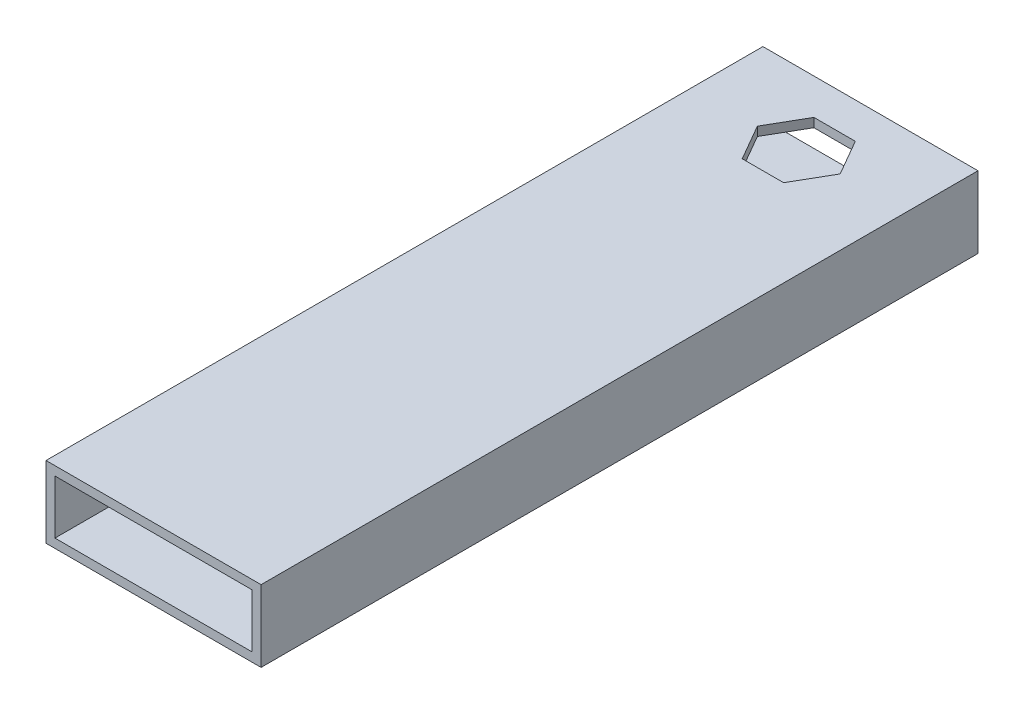
SolidWorks part; units mm, degrees
material "6061 Alloy"
ref_plane "Front Plane" through (0, 0, 0) normal (0, 0, 1) x (1, 0, 0)
ref_plane "Top Plane" through (0, 0, 0) normal (0, 1, 0) x (1, 0, 0)
ref_plane "Right Plane" through (0, 0, 0) normal (1, 0, 0) x (0, 0, -1)
sketch "Sketch1" plane through (0, 0, 0) normal (0, 0, 1) x (1, 0, 0)
  line L1 (0, 0) -> (38.1, 0)
  line L2 (0, 0) -> (0, 12.7)
  line L3 (0, 12.7) -> (38.1, 12.7)
  line L4 (38.1, 0) -> (38.1, 12.7)
  dimension "D1" = 38.1
  dimension "D2" = 12.7
extrude "Boss-Extrude1" add sketch "Sketch1" along normal blind 127
sketch "Sketch2" plane through (0, 0, 127) normal (0, 0, 1) x (1, 0, 0)
  line L4 (36.5125, 1.5875) -> (36.5125, 11.1125)
  line L5 (36.5125, 1.5875) -> (36.5125, 11.1125)
  line L6 (1.5875, 11.1125) -> (1.5875, 1.5875)
  line L7 (1.5875, 11.1125) -> (1.5875, 1.5875)
  line L8 (36.5125, 11.1125) -> (1.5875, 11.1125)
  line L9 (1.5875, 1.5875) -> (36.5125, 1.5875)
  line L10 (36.5125, 11.1125) -> (1.5875, 11.1125)
  line L13 (1.5875, 1.5875) -> (36.5125, 1.5875)
  dimension "D1" = 1.5875
extrude "Cut-Extrude1" cut sketch "Sketch2" against normal through all
sketch "Sketch3" plane through (0, 0, 0) normal (0, -1, 0) x (1, 0, 0)
  line L3 (26.3823, 12.7) -> (22.7162, 19.05)
  line L4 (22.7162, 19.05) -> (15.3838, 19.05)
  line L5 (15.3838, 19.05) -> (11.7177, 12.7)
  line L6 (11.7177, 12.7) -> (15.3838, 6.35)
  line L7 (15.3838, 6.35) -> (22.7162, 6.35)
  line L8 (22.7162, 6.35) -> (26.3823, 12.7)
  line L9 (38.1, 127) -> (38.1, 0) construction
  line L10 (0, 0) -> (38.1, 0) construction
  circle A0 centre (19.05, 12.7) radius 6.35 construction
  dimension "D3" = 12.7
  dimension "D1" = 12.7
  dimension "D2" = 19.05
extrude "Cut-Extrude2" cut sketch "Sketch3" against normal through all
